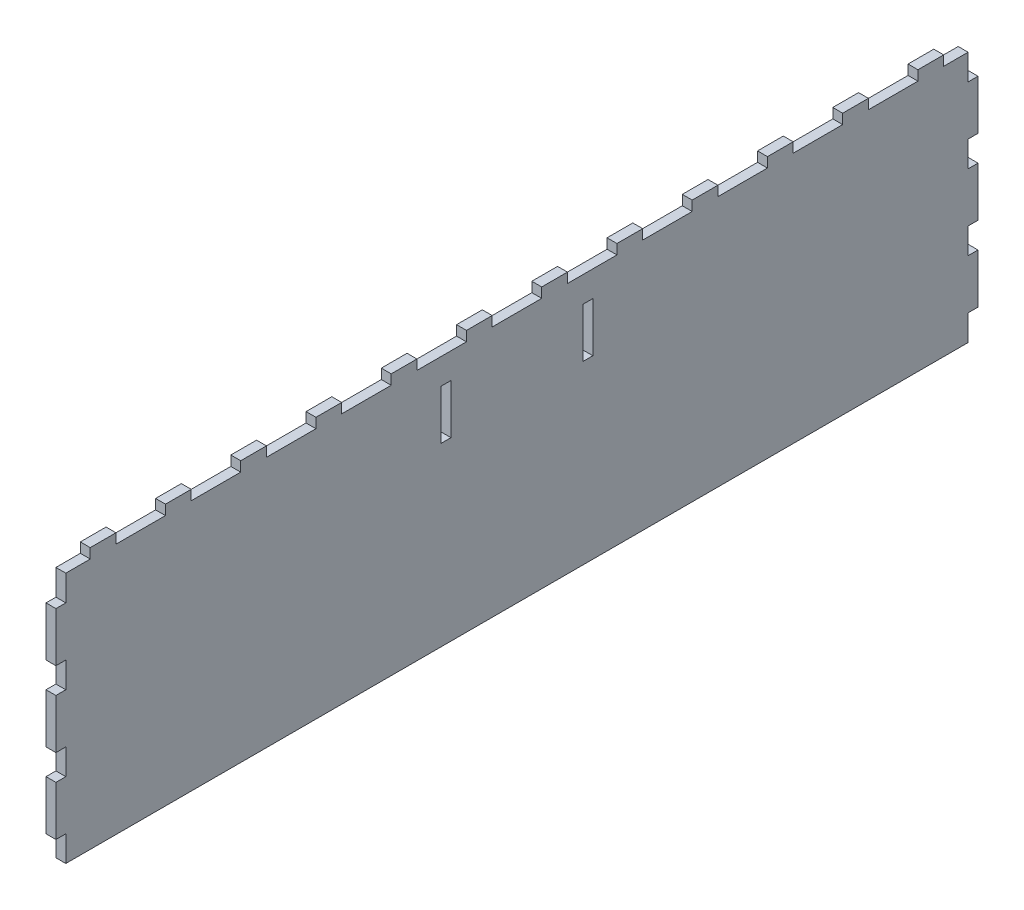
SolidWorks part; units mm, degrees
material "ENPH 253 Hardboard"
ref_plane "Front Plane" through (0, 0, 0) normal (0, 0, 1) x (1, 0, 0)
ref_plane "Top Plane" through (0, 0, 0) normal (0, 1, 0) x (1, 0, 0)
ref_plane "Right Plane" through (0, 0, 0) normal (1, 0, 0) x (0, 0, -1)
sketch "Sketch1" plane through (0, 0, 0) normal (1, 0, 0) x (0, 0, -1)
  line L1 (-139.7, 38.1) -> (139.7, 38.1)
  line L2 (-139.7, 38.1) -> (-139.7, -38.1)
  line L3 (-139.7, -38.1) -> (139.7, -38.1)
  line L4 (139.7, 38.1) -> (139.7, -38.1)
  line L5 (-139.7, 38.1) -> (139.7, -38.1) construction
  line L6 (-139.7, -38.1) -> (139.7, 38.1) construction
  point P0 (0, 0)
  dimension "D1" = 279.4
  dimension "D2" = 76.2
extrude "Boss-Extrude1" add sketch "Sketch1" against normal blind 3 contours L2 L3 L4 L1
sketch "Sketch3" plane through (-3, 0, 0) normal (-1, 0, 0) x (0, 0, 1)
  line L9 (-139.7, 38.1) -> (-136.7, 38.1)
  line L10 (-139.7, 38.1) -> (-139.7, 30.3)
  line L11 (-139.7, 30.3) -> (-136.7, 30.3)
  line L12 (-136.7, 38.1) -> (-136.7, 30.3)
  dimension "D9" = 7.8
  dimension "D10" = 3
extrude "Cut-Extrude1" cut sketch "Sketch3" against normal through all
pattern_linear "LPattern1" count 4 spacing 22.8 along (0, -1, 0) of "Cut-Extrude1"
mirror "Mirror1" about plane through (0, 0, 0) normal (0, 0, 1) of "LPattern1", "Cut-Extrude1"
sketch "Sketch5" plane through (-3, 0, 0) normal (-1, 0, 0) x (0, 0, 1)
  line L1 (-23, 30.3) -> (-20, 30.3)
  line L2 (-23, 30.3) -> (-23, 15.3)
  line L3 (-23, 15.3) -> (-20, 15.3)
  line L4 (-20, 30.3) -> (-20, 15.3)
  line L5 (136.7, 38.1) -> (-136.7, 38.1) construction
  line L6 (0, -1.65) -> (0, 1.65) construction
  dimension "D1" = 20
  dimension "D2" = 3
  dimension "D3" = 7.8
  dimension "D4" = 15
extrude "Cut-Extrude3" cut sketch "Sketch5" against normal blind 10
mirror "Mirror2" about plane through (0, 0, 0) normal (0, 0, 1) of "Cut-Extrude3"
sketch "Sketch9" plane through (0, 38.1, 0) normal (0, 1, 0) x (1, 0, 0)
  line L0 (0, -136.7) -> (0, 136.7) construction
  line L1 (0, 129.3) -> (-3, 129.3)
  line L2 (0, 129.3) -> (0, 121.5)
  line L3 (0, 121.5) -> (-3, 121.5)
  line L4 (-3, 129.3) -> (-3, 121.5)
  line L5 (-3, -136.7) -> (-3, 136.7) construction
  line L6 (0, 136.7) -> (-3, 136.7) construction
  point P10 (-1.5, 129.3)
  dimension "D1" = 7.4
  dimension "D2" = 7.8
extrude "Boss-Extrude2" add sketch "Sketch9" along normal blind 3
pattern_linear "LPattern4" count 12 spacing 22.8 along (0, 0, 1) of "Boss-Extrude2"
